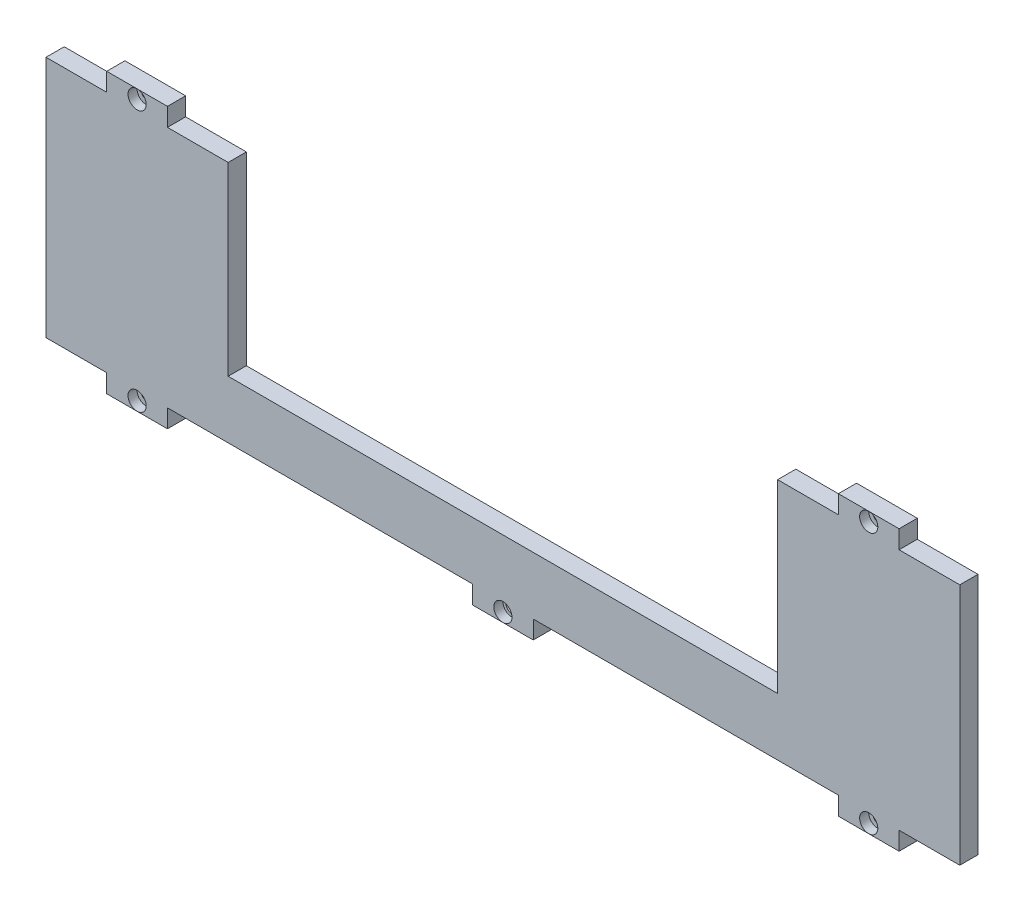
SolidWorks part; units mm, degrees
ref_plane "Plan de face" through (0, 0, 0) normal (0, 0, 1) x (1, 0, 0)
ref_plane "Plan de dessus" through (0, 0, 0) normal (0, 1, 0) x (1, 0, 0)
ref_plane "Plan de droite" through (0, 0, 0) normal (1, 0, 0) x (0, 0, -1)
sketch "Esquisse1" plane through (0, 0, 0) normal (0, 0, 1) x (1, 0, 0)
  line L0 (-301, 80) -> (-281, 80)
  line L1 (0, 0) -> (-20, 0)
  line L2 (0, 0) -> (0, 80)
  line L3 (-301, -6) -> (0, -6) construction
  line L4 (-301, 0) -> (-301, 80)
  line L5 (-281, 0) -> (-301, 0)
  line L6 (-160.5, 0) -> (-261, 0)
  line L7 (-281, 0) -> (-281, -6)
  line L8 (-281, -6) -> (-261, -6)
  line L9 (-261, 0) -> (-261, -6)
  line L10 (-40, 0) -> (-140.5, 0)
  line L11 (-160.5, 0) -> (-160.5, -6)
  line L12 (-160.5, -6) -> (-140.5, -6)
  line L13 (-140.5, 0) -> (-140.5, -6)
  line L14 (-301, 40) -> (0, 40) construction
  line L15 (-40, 0) -> (-40, -6)
  line L16 (-40, -6) -> (-20, -6)
  line L17 (-20, 0) -> (-20, -6)
  line L18 (-261, 80) -> (-261, 86)
  line L19 (-281, 86) -> (-261, 86)
  line L20 (-281, 80) -> (-281, 86)
  line L21 (-20, 80) -> (-20, 86)
  line L22 (-40, 86) -> (-20, 86)
  line L23 (-40, 80) -> (-40, 86)
  line L24 (-20, 80) -> (0, 80)
  line L25 (-261, 80) -> (-40, 80)
  dimension "D1" = 80
  dimension "D2" = 301
  dimension "D3" = 6
  dimension "D4" = 20
  dimension "D5" = 20
  dimension "D6" = 20
  dimension "D7" = 20
  dimension "D8" = 100.5
  dimension "D9" = 20
extrude "Boss.-Extru.1" add sketch "Esquisse1" along normal blind 6
sketch "Esquisse2" plane through (0, 0, 6) normal (0, 0, 1) x (1, 0, 0)
  line L1 (-241, 80) -> (-60, 80)
  line L2 (-241, 80) -> (-241, 19)
  line L3 (-241, 19) -> (-60, 19)
  line L4 (-60, 80) -> (-60, 19)
  line L6 (-301, 80) -> (-301, 0) construction
  line L8 (-40, 80) -> (-261, 80) construction
  dimension "D1" = 181
  dimension "D2" = 61
  dimension "D3" = 0
  dimension "D4" = 60
extrude "Enlèv. mat.-Extru.1" cut sketch "Esquisse2" against normal through all
sketch "Esquisse4" plane through (0, 0, 6) normal (0, 0, 1) x (1, 0, 0)
  line L1 (-281, 86) -> (-281, 80) construction
  line L2 (-301, 40) -> (0, 40) construction
  line L3 (-301, 80) -> (-301, 0) construction
  line L4 (-20, 80) -> (-20, 86) construction
  line L5 (-20, 86) -> (-40, 86) construction
  line L6 (-261, 86) -> (-281, 86) construction
  line L7 (0, 0) -> (0, 80) construction
  line L8 (-160.5, -6) -> (-140.5, -6) construction
  line L9 (-160.5, 0) -> (-160.5, -6) construction
  circle A0 centre (-271, 83) radius 1.5
  circle A1 centre (-30, 83) radius 1.5
  circle A2 centre (-30, -3) radius 1.5
  circle A3 centre (-271, -3) radius 1.5
  circle A4 centre (-150.5, -3) radius 2.0374
  point P26 (-160.5, -3)
  point P28 (0, 0)
  dimension "D1" = 3
  dimension "D2" = 3
  dimension "D3" = 10
  dimension "D4" = 3
  dimension "D5" = 3
  dimension "D6" = 10
  dimension "D7" = 3
  dimension "D8" = 10
extrude "Enlèv. mat.-Extru.2" cut sketch "Esquisse4" against normal through all
sketch "Esquisse5" plane through (0, 0, 6) normal (0, 0, 1) x (1, 0, 0)
  circle A0 centre (-271, 83) radius 2.995
  circle A1 centre (-30, 83) radius 2.995
  circle A3 centre (-271, -3) radius 2.995
  circle A4 centre (-150.5, -3) radius 2.995
  circle A5 centre (-30, -3) radius 2.995
  dimension "D1" = 5.99
  dimension "D2" = 5.99
  dimension "D3" = 5.99
  dimension "D4" = 5.99
  dimension "D5" = 5.99
extrude "Enlèv. mat.-Extru.3" cut sketch "Esquisse5" against normal blind 3
